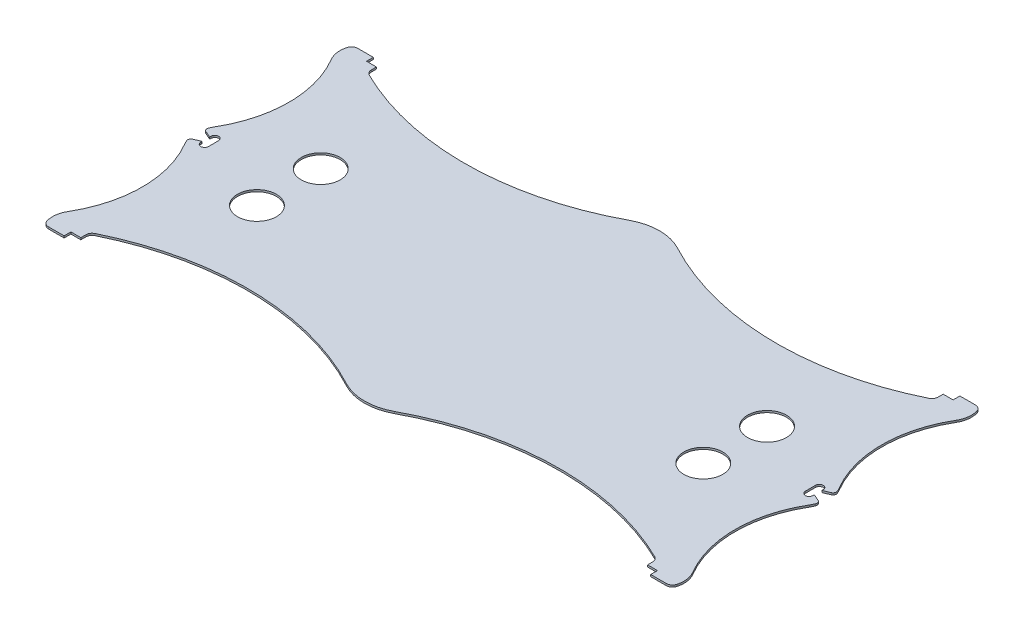
SolidWorks part; units mm, degrees
material "Copper"
ref_plane "Front Plane" through (0, 0, 0) normal (0, 0, 1) x (1, 0, 0)
ref_plane "Top Plane" through (0, 0, 0) normal (0, 1, 0) x (1, 0, 0)
ref_plane "Right Plane" through (0, 0, 0) normal (1, 0, 0) x (0, 0, -1)
sketch "Sketch1" plane through (0, 0, 0) normal (0, 1, 0) x (1, 0, 0)
  line L0 (-49, 23) -> (49, -23) construction
  line L1 (-46, 24.2465) -> (-48.4276, 24.2465)
  line L2 (-46, 23.1792) -> (-46, 24.2465)
  line L3 (-44.447, 23.1792) -> (-46, 23.1792)
  line L4 (-44.447, 22.3994) -> (-44.447, 23.1792)
  line L5 (0, 53.1149) -> (0, -61.177) construction
  line L6 (24.5, 69.002) -> (24.5, -61.177) construction
  line L7 (44.447, 22.3994) -> (44.447, 23.1792)
  line L8 (44.447, 23.1792) -> (46, 23.1792)
  line L9 (46, 23.1792) -> (46, 24.2465)
  line L10 (46, 24.2465) -> (48.4276, 24.2465)
  line L11 (-53.3541, 0) -> (101.2526, 0) construction
  line L12 (34.9616, 11.5) -> (61.8373, 11.5) construction
  line L13 (46, -24.2465) -> (48.4276, -24.2465)
  line L14 (46, -23.1792) -> (46, -24.2465)
  line L15 (44.447, -23.1792) -> (46, -23.1792)
  line L16 (44.447, -22.3994) -> (44.447, -23.1792)
  line L17 (-44.447, -22.3994) -> (-44.447, -23.1792)
  line L18 (-44.447, -23.1792) -> (-46, -23.1792)
  line L19 (-46, -23.1792) -> (-46, -24.2465)
  line L20 (-46, -24.2465) -> (-48.4276, -24.2465)
  arc A0 (3.7692, 22.1898) -> (43.8877, 21.5017) centre (24.5, 61) ccw
  arc A1 (49, 20.6515) -> (49, 2.3485) centre (64.5, 11.5) ccw
  arc A2 (49, 20.6515) -> (49.3944, 23.502) centre (45.7867, 22.5487) ccw
  arc A3 (48.4276, 24.2465) -> (49.3944, 23.502) centre (48.4276, 23.2465) cw
  arc A4 (-3.7692, 22.1898) -> (-43.8877, 21.5017) centre (-24.5, 61) cw
  arc A5 (-49, 20.6515) -> (-49, 2.3485) centre (-64.5, 11.5) cw
  arc A6 (-49, 20.6515) -> (-49.3944, 23.502) centre (-45.7867, 22.5487) cw
  arc A7 (-48.4276, 24.2465) -> (-49.3944, 23.502) centre (-48.4276, 23.2465) ccw
  arc A8 (-3.7692, 22.1898) -> (3.7692, 22.1898) centre (0, 15.1333) cw
  arc A9 (-3.7692, -22.1898) -> (3.7692, -22.1898) centre (0, -15.1333) ccw
  arc A10 (-48.4276, -24.2465) -> (-49.3944, -23.502) centre (-48.4276, -23.2465) cw
  arc A11 (-49, -20.6515) -> (-49.3944, -23.502) centre (-45.7867, -22.5487) ccw
  arc A12 (-49, -20.6515) -> (-49, -2.3485) centre (-64.5, -11.5) ccw
  arc A13 (-3.7692, -22.1898) -> (-43.8877, -21.5017) centre (-24.5, -61) ccw
  arc A14 (48.4276, -24.2465) -> (49.3944, -23.502) centre (48.4276, -23.2465) ccw
  arc A15 (49, -20.6515) -> (49.3944, -23.502) centre (45.7867, -22.5487) cw
  arc A16 (49, -20.6515) -> (49, -2.3485) centre (64.5, -11.5) cw
  arc A17 (3.7692, -22.1898) -> (43.8877, -21.5017) centre (24.5, -61) cw
  arc A18 (49, 2.3485) -> (49, -2.3485) centre (45.0223, 0) cw
  arc A19 (-49, 2.3485) -> (-49, -2.3485) centre (-45.0223, 0) ccw
  arc A20 (43.8877, 21.5017) -> (44.447, 22.3994) centre (43.447, 22.3994) ccw
  arc A21 (-43.8877, 21.5017) -> (-44.447, 22.3994) centre (-43.447, 22.3994) cw
  arc A22 (-43.8877, -21.5017) -> (-44.447, -22.3994) centre (-43.447, -22.3994) ccw
  arc A23 (43.8877, -21.5017) -> (44.447, -22.3994) centre (43.447, -22.3994) cw
  point P69 (44.447, 21.7812)
  point P72 (-44.447, 21.7812)
  point P75 (-44.447, -21.7812)
  point P78 (44.447, -21.7812)
  dimension "D5" = 88
  dimension "D2" = 36
  dimension "D7" = 1
  dimension "D9" = 1
  dimension "D10" = 1
  dimension "D11" = 8
  dimension "D1" = 11.5
  dimension "D3" = 24.5
  dimension "D4" = 61
  dimension "D6" = 40
  dimension "D8" = 46
extrude "Boss-Extrude1" add sketch "Sketch1" along normal blind 0.3
sketch "Sketch2" plane through (0, 0.3, 0) normal (0, 1, 0) x (1, 0, 0)
  line L0 (-61.084, 0) -> (64.942, 0) construction
  line B0 (47.4082, 0.8) -> (47.4082, -1.2) construction
  line B1 (48.0082, 0.5958) -> (51.1609, 1.9416)
  line B2 (46.8082, 0.8) -> (46.8082, -0.8)
  line B3 (48.0082, -0.8) -> (48.0082, -0.5958)
  line B4 (48.0082, 0.8) -> (48.0082, 0.5958)
  line B5 (48.0082, -0.5958) -> (51.1609, -1.9416)
  line B6 (51.1609, 1.9416) -> (51.1609, -1.9416)
  arc B7 (48.0082, 0.8) -> (46.8082, 0.8) centre (47.4082, 0.8) ccw
  arc B8 (48.0082, -0.8) -> (46.8082, -0.8) centre (47.4082, -0.8) cw
sketch_block_instance "Block1-1"
sketch_block "Block1" parameters "D1"=0.8
extrude "Cut-Extrude1" cut sketch "Sketch2" against normal blind 0.3
sketch "Sketch3" plane through (0, 0.3, 0) normal (0, 1, 0) x (1, 0, 0)
  line L0 (-57.9383, 0) -> (58.7523, 0) construction
  circle A0 centre (35, 5) radius 3.05
  circle A1 centre (35, -5) radius 3.05
  dimension "D3" = 6.1
  dimension "D1" = 35
  dimension "D2" = 5
extrude "Cut-Extrude2" cut sketch "Sketch3" against normal blind 10
mirror "Mirror2" about plane through (0, 0, 0) normal (1, 0, 0) of "Cut-Extrude1", "Cut-Extrude2"
fillet "Fillet3" radius 0.5 4 edges at (49.4768, 0.15, -1.2227) (49.4768, 0.15, 1.2227) (-49.4768, 0.15, 1.2227) (-49.4768, 0.15, -1.2227)
